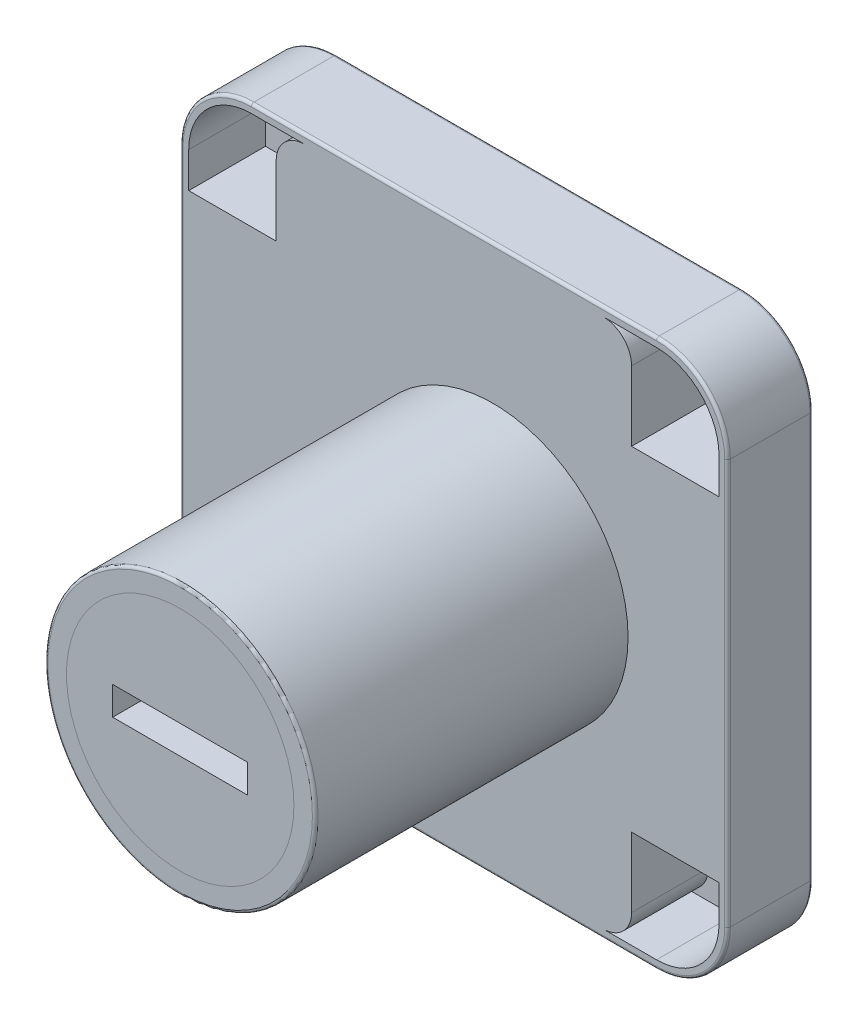
SolidWorks part; units mm, degrees
ref_plane "前视基准面" through (0, 0, 0) normal (0, 0, 1) x (1, 0, 0)
ref_plane "上视基准面" through (0, 0, 0) normal (0, 1, 0) x (1, 0, 0)
ref_plane "右视基准面" through (0, 0, 0) normal (1, 0, 0) x (0, 0, -1)
sketch "草图1" plane through (0, 0, 0) normal (0, 0, 1) x (1, 0, 0)
  line L1 (-19.25, 19.25) -> (19.25, 19.25)
  line L2 (-19.25, 19.25) -> (-19.25, -19.25)
  line L3 (-19.25, -19.25) -> (19.25, -19.25)
  line L4 (19.25, 19.25) -> (19.25, -19.25)
  point P4 (0, 19.25)
  point P6 (19.25, 0)
  dimension "D1" = 38.5
  dimension "D2" = 38.5
extrude "凸台-拉伸1" add sketch "草图1" along normal blind 6
fillet "圆角1" radius 5 4 edges at (-19.25, -19.25, 3) (19.25, -19.25, 3) (19.25, 19.25, 3) (-19.25, 19.25, 3)
shell "抽壳1" thickness 0.6
sketch "草图2" plane through (0, 0, 6) normal (0, 0, 1) x (1, 0, 0)
  line L0 (-12.5, 16.65) -> (-12.5, 11.75)
  line L1 (-12.5, 11.75) -> (-18.65, 11.75)
  line L2 (-18.65, 11.75) -> (-18.65, -11.75)
  line L3 (-18.65, -11.75) -> (-12.5, -11.75)
  line L4 (-12.5, -11.75) -> (-12.5, -16.65)
  line L5 (-14.25, -18.65) -> (14.25, -18.65) construction
  line L6 (-10.5, -18.65) -> (10.5, -18.65)
  line L7 (12.5, -16.65) -> (12.5, -11.75)
  line L8 (12.5, -11.75) -> (18.65, -11.75)
  line L9 (18.65, -11.75) -> (18.65, 11.75)
  line L10 (18.65, 11.75) -> (12.5, 11.75)
  line L11 (12.5, 11.75) -> (12.5, 16.65)
  line L12 (10.5, 18.65) -> (-10.5, 18.65)
  line L13 (18.65, -14.25) -> (18.65, 14.25) construction
  line L14 (14.25, 18.65) -> (-14.25, 18.65) construction
  line L15 (-18.65, 14.25) -> (-18.65, -14.25) construction
  line L16 (0, 0) -> (0, -13.1851) construction
  line L17 (0, 0) -> (12.0906, 0) construction
  arc A0 (-10.5, -18.65) -> (-12.5, -16.65) centre (-10.5, -16.65) cw
  arc A1 (10.5, -18.65) -> (12.5, -16.65) centre (10.5, -16.65) ccw
  arc A2 (10.5, 18.65) -> (12.5, 16.65) centre (10.5, 16.65) cw
  arc A3 (-10.5, 18.65) -> (-12.5, 16.65) centre (-10.5, 16.65) ccw
  point P27 (-12.5, -18.65)
  point P30 (12.5, -18.65)
  dimension "D2" = 2
  dimension "D1" = 25
  dimension "D3" = 23.5
extrude "凸台-拉伸2" add sketch "草图2" against normal up to surface (5.4 mm away) separate body up to face at (0, 0, 0.6)
sketch "草图3" plane through (0, 0, 6) normal (0, 0, 1) x (1, 0, 0)
  line L0 (19.25, -14.25) -> (19.25, 14.25) construction
  circle A0 centre (2.75, 0) radius 9.5
  dimension "D1" = 19
  dimension "D2" = 16.5
extrude "拉伸-薄壁1" add sketch "草图3" along normal blind 22 thin thin type one direction reverse wall 1.5
sketch "草图4" plane through (0, 0, 28) normal (0, 0, 1) x (1, 0, 0)
  circle A0 centre (2.75, 0) radius 8
  circle A1 centre (2.75, 0) radius 8 construction
extrude "凸台-拉伸3" add sketch "草图4" against normal blind 22 separate body
sketch "草图5" plane through (0, 0, 28) normal (0, 0, 1) x (1, 0, 0)
  line L0 (2.75, 8) -> (2.75, -8) construction
  line L1 (-2, 1) -> (7.5, 1)
  line L2 (-2, 1) -> (-2, -1)
  line L3 (-2, -1) -> (7.5, -1)
  line L4 (7.5, 1) -> (7.5, -1)
  circle A0 centre (2.75, 0) radius 8 construction
  circle A1 centre (2.75, 0) radius 8 construction
  point P4 (-2, 0)
  point P13 (2.75, 1)
  dimension "D1" = 2
  dimension "D2" = 9.5
extrude "切除-拉伸1" cut sketch "草图5" against normal blind 5
fillet "圆角2" radius 0.2 17 edges at (12.25, 0, 28) (-17.7855, 17.7855, 0) (0, 19.25, 0) (17.7855, 17.7855, 0) (19.25, 0, 0) (17.7855, -17.7855, 0) (0, -19.25, 0) (-17.7855, -17.7855, 0) (-17.7855, 17.7855, 6) (0, 19.25, 6) (17.7855, 17.7855, 6) (19.25, 0, 6) (17.7855, -17.7855, 6) (0, -19.25, 6) (-17.7855, -17.7855, 6) (-19.25, 0, 0) (-19.25, 0, 6)
sketch "草图6" plane through (0, 0, 0) normal (0, 0, -1) x (-1, 0, 0)
  line L0 (0, 9.7239) -> (0, 0) construction
  line L1 (0, 0) -> (9.505, 0) construction
  circle A0 centre (-15, 15) radius 2.5
  circle A1 centre (15, 15) radius 2.5
  circle A2 centre (15, -15) radius 2.5
  circle A3 centre (-15, -15) radius 2.5
  dimension "D2" = 5
  dimension "D3" = 30
  dimension "D1" = 30
extrude "切除-拉伸2" cut sketch "草图6" against normal blind 10
